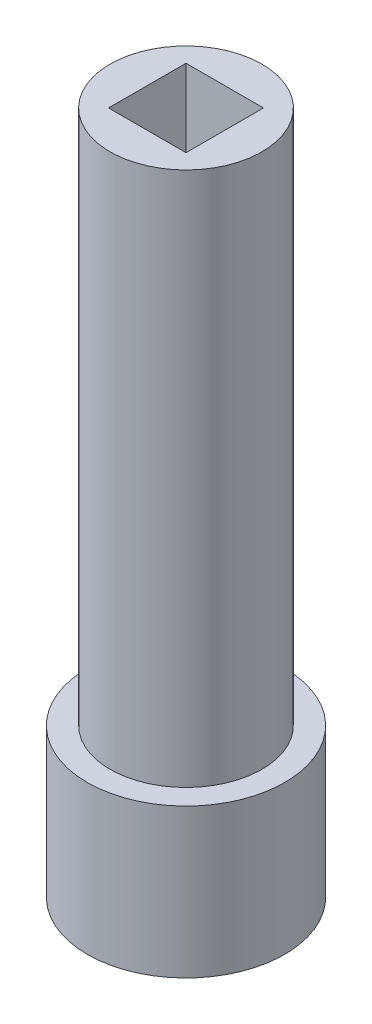
SolidWorks part; units mm, degrees
ref_plane "Front Plane" through (0, 0, 0) normal (0, 0, 1) x (1, 0, 0)
ref_plane "Top Plane" through (0, 0, 0) normal (0, 1, 0) x (1, 0, 0)
ref_plane "Right Plane" through (0, 0, 0) normal (1, 0, 0) x (0, 0, -1)
sketch "Sketch1" plane through (0, 0, 0) normal (0, 1, 0) x (1, 0, 0)
  circle A0 centre (0, 0) radius 5
  dimension "D1" = 10
extrude "Boss-Extrude1" add sketch "Sketch1" along normal blind 45
sketch "Sketch2" plane through (0, 45, 0) normal (0, 1, 0) x (1, 0, 0)
  line L1 (-2.55, 2.55) -> (2.55, 2.55)
  line L2 (-2.55, 2.55) -> (-2.55, -2.55)
  line L3 (-2.55, -2.55) -> (2.55, -2.55)
  line L4 (2.55, 2.55) -> (2.55, -2.55)
  circle A0 centre (0, 0) radius 5 construction
  dimension "D3" = 2.55
  dimension "D1" = 2.55
  dimension "D2" = 2.55
  dimension "D4" = 2.55
extrude "Cut-Extrude1" cut sketch "Sketch2" against normal blind 22
sketch "Sketch3" plane through (0, 0, 0) normal (0, -1, 0) x (1, 0, 0)
  circle A0 centre (0, 0) radius 6.5
  dimension "D1" = 13
extrude "Boss-Extrude2" add sketch "Sketch3" against normal blind 9.8
